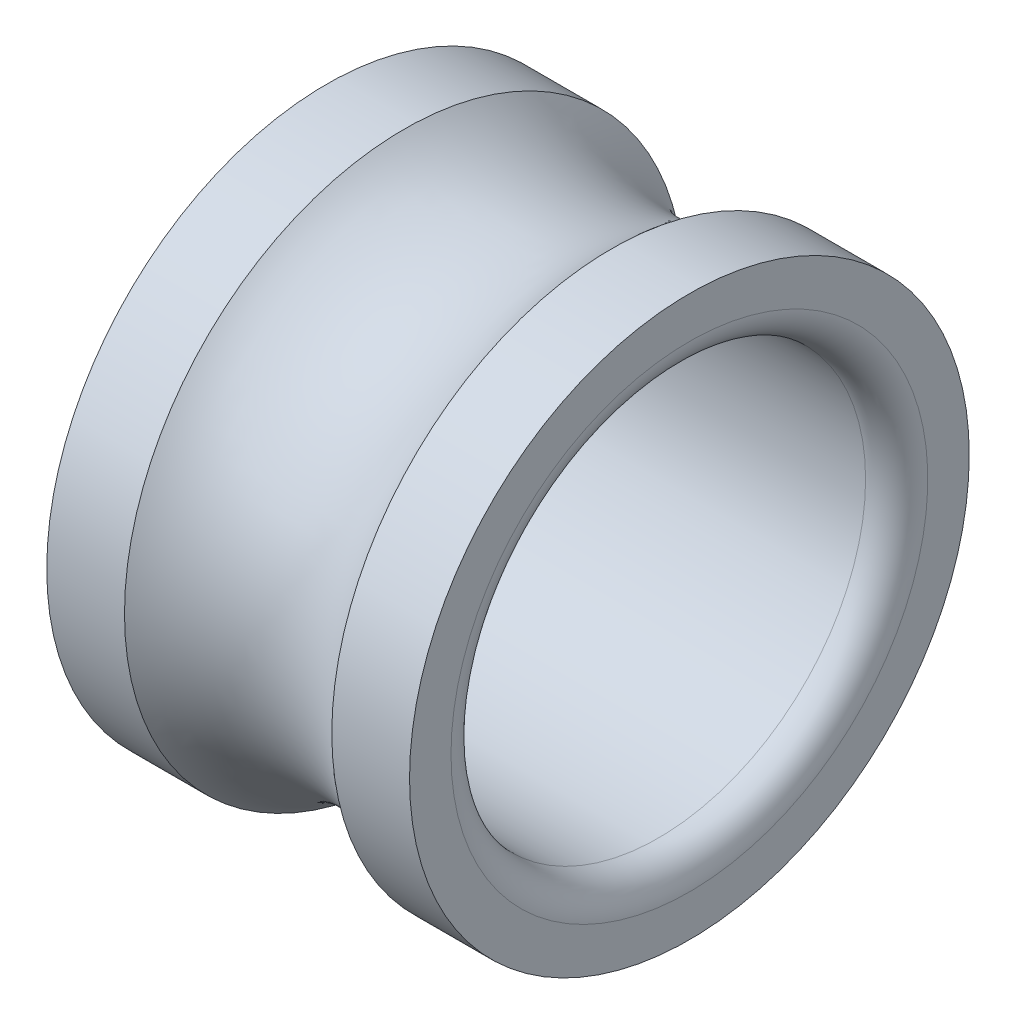
SolidWorks part; units mm, degrees
material "Dövülebilir Dökme Demir"
ref_plane "Ön Düzlem" through (0, 0, 0) normal (0, 0, 1) x (1, 0, 0)
ref_plane "Üst Düzlem" through (0, 0, 0) normal (0, 1, 0) x (1, 0, 0)
ref_plane "Sağ Düzlem" through (0, 0, 0) normal (1, 0, 0) x (0, 0, -1)
sketch "Çizim1" plane through (0, 0, 0) normal (0, 0, 1) x (1, 0, 0)
  line L0 (0, 0) -> (0, 4.7) construction
  line L1 (-20.1487, 0) -> (15.9193, 0) construction
  line L8 (3.5, 5.4) -> (3.5, 4.6)
  line L9 (2.9, 4) -> (-2.9, 4)
  line L10 (-3.5, 5.4) -> (-3.5, 4.6)
  line L11 (3.5, 5.4) -> (-3.5, 4) construction
  line L12 (3.5, 4) -> (-3.5, 5.4) construction
  line L14 (-3.5, 5.4) -> (-2, 5.4)
  line L15 (3.5, 5.4) -> (2, 5.4)
  arc A0 (2, 5.4) -> (-2, 5.4) centre (0, 7.6361) cw
  arc A1 (-3.5, 4.6) -> (-2.9, 4) centre (-2.9, 4.6) ccw
  arc A2 (2.9, 4) -> (3.5, 4.6) centre (2.9, 4.6) ccw
  dimension "D5" = 0.6
  dimension "D1" = 4
  dimension "D2" = 5.4
  dimension "D3" = 7
revolve "Döndür1" add sketch "Çizim1" angle 360 about L1
